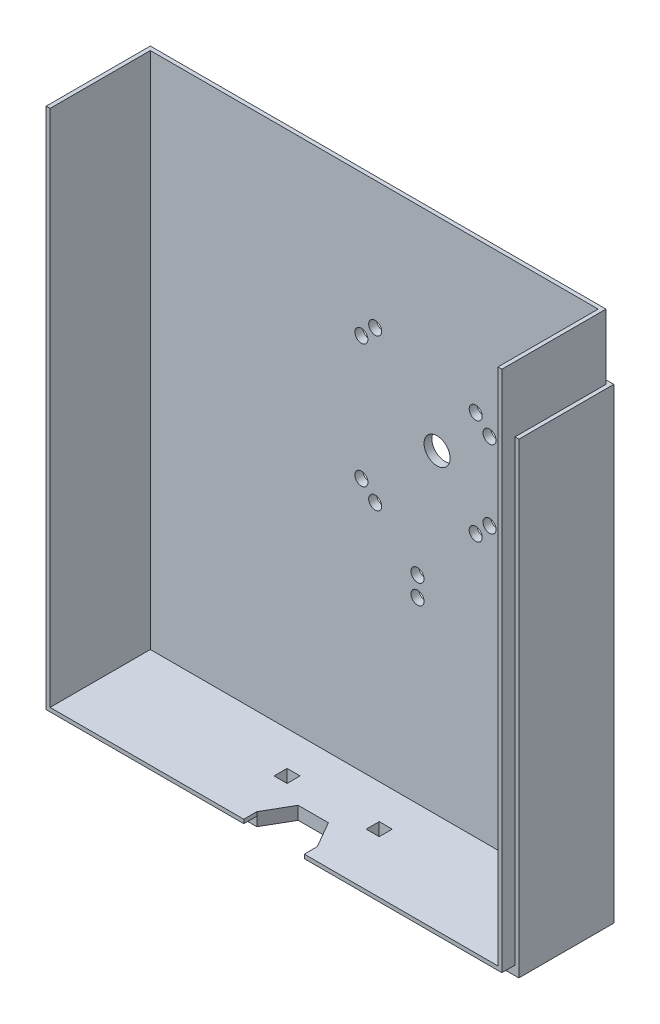
SolidWorks part; units mm, degrees
ref_plane "Front Plane" through (0, 0, 0) normal (0, 0, 1) x (1, 0, 0)
ref_plane "Top Plane" through (0, 0, 0) normal (0, 1, 0) x (1, 0, 0)
ref_plane "Right Plane" through (0, 0, 0) normal (1, 0, 0) x (0, 0, -1)
sketch "Sketch1" plane through (0, 0, 0) normal (0, 0, 1) x (1, 0, 0)
  line L1 (-88.9, -127) -> (88.9, -127)
  line L2 (-88.9, -127) -> (-88.9, 127)
  line L3 (-88.9, 127) -> (88.9, 127)
  line L4 (88.9, -127) -> (88.9, 127)
  line L5 (-88.9, -127) -> (88.9, 127) construction
  line L6 (-88.9, 127) -> (88.9, -127) construction
  point P0 (0, 0)
  dimension "D1" = 177.8
  dimension "D2" = 254
extrude "Boss-Extrude1" add sketch "Sketch1" along normal mid plane 72.89
shell "Shell1" thickness 3
sketch "Sketch2" plane through (0, 0, 33.445) normal (0, 0, -1) x (-1, 0, 0)
  line L0 (85.9, -124) -> (-85.9, -124) construction
  circle A0 centre (0, -4) radius 22
  dimension "D1" = 44
  dimension "D2" = 120
extrude "Cut-Extrude1" cut sketch "Sketch2" against normal blind 3
sketch "Sketch3" plane through (0, 0, -33.445) normal (0, 0, 1) x (1, 0, 0)
  line L0 (85.9, 124) -> (-85.9, 124) construction
  line L1 (-85.9, 124) -> (-85.9, -124) construction
  line L2 (44.2293, 13.826) -> (38.926, 19.1293) construction
  line L3 (-975.9, -1) -> (49024.1, -1) construction
  line L4 (24.1, -1) -> (41.5777, 16.4777) construction
  line L5 (-4.9352, 22.7319) -> (0.3681, 28.0352) construction
  line L6 (24.1, -1) -> (-2.2836, 25.3836) construction
  circle A0 centre (24.1, -1) radius 5
  circle A1 centre (24.1, -1) radius 25 construction
  circle A2 centre (44.2293, 13.826) radius 2.5
  circle A3 centre (38.926, 19.1293) radius 2.5
  circle A4 centre (38.926, -21.1293) radius 2.5
  circle A5 centre (44.2293, -15.826) radius 2.5
  circle A6 centre (24.1, -1) radius 37.5 construction
  circle A7 centre (0.3681, 28.0352) radius 2.5
  circle A8 centre (-4.9352, 22.7319) radius 2.5
  circle A9 centre (-4.9352, -24.7319) radius 2.5
  circle A10 centre (0.3681, -30.0352) radius 2.5
  circle A11 centre (16.6, -46) radius 2.5
  circle A12 centre (16.6, -53.5) radius 2.5
  dimension "D3" = 10
  dimension "D4" = 50
  dimension "D5" = 5
  dimension "D8" = 75
  dimension "D9" = 7.5
  dimension "D11" = 7.5
  dimension "D13" = 45
  dimension "D1" = 125
  dimension "D2" = 110
  dimension "D6" = 7.5
  dimension "D7" = 45
  dimension "D10" = 45
  dimension "D12" = 7.5
extrude "Cut-Extrude2" cut sketch "Sketch3" against normal blind 3
sketch "Sketch12" plane through (0, 124, 0) normal (0, -1, 0) x (1, 0, 0)
  line L0 (85.9, -33.445) -> (-85.9, -33.445) construction
  line L1 (6, 33.445) -> (-6, 33.445)
  line L2 (6, 33.445) -> (6, -33.445)
  line L3 (6, -33.445) -> (-6, -33.445)
  line L4 (-6, 33.445) -> (-6, -33.445)
  line L5 (6, 33.445) -> (-6, -33.445) construction
  line L6 (6, -33.445) -> (-6, 33.445) construction
  point P0 (0, 0)
  dimension "D1" = 12
extrude "Boss-Extrude5" add sketch "Sketch12" along normal blind 8
sketch "Sketch10" plane through (0, 127, 0) normal (0, 1, 0) x (1, 0, 0)
  circle A0 centre (0, 0) radius 3
  dimension "D1" = 6
extrude "Cut-Extrude8" cut sketch "Sketch10" against normal blind 8 contours A0
ref_plane "Plane2" through (0, 52, 0) normal (0, 1, 0) x (1, 0, 0)
split "Split2" trim tools "Plane2" bodies to split 123 resulting bodies 126 127
sketch "Sketch13" plane through (0, 52, 0) normal (0, 1, 0) x (1, 0, 0)
  line L4 (-85.9, 33.445) -> (-85.9, -33.445)
  line L5 (-85.9, -33.445) -> (85.9, -33.445)
  line L6 (85.9, -33.445) -> (85.9, 33.445)
  line L7 (85.9, 33.445) -> (-85.9, 33.445)
  line L8 (-87.4, 34.945) -> (-87.4, -34.945)
  line L9 (-87.4, -34.945) -> (87.4, -34.945)
  line L10 (87.4, -34.945) -> (87.4, 34.945)
  line L11 (87.4, 34.945) -> (-87.4, 34.945)
  line L12 (-87.4, 34.945) -> (-87.4, -34.945)
  line L13 (-87.4, -34.945) -> (87.4, -34.945)
  line L14 (87.4, -34.945) -> (87.4, 34.945)
  line L15 (87.4, 34.945) -> (-87.4, 34.945)
  dimension "D1" = 1.5
  dimension "D2" = 1.5
extrude "Boss-Extrude6" add sketch "Sketch13" along normal blind 25
sketch "Sketch14" plane through (0, 52, 0) normal (0, -1, 0) x (1, 0, 0)
  line L7 (-85.9, 33.445) -> (-85.9, -33.445)
  line L8 (-85.9, -33.445) -> (85.9, -33.445)
  line L9 (85.9, -33.445) -> (85.9, 33.445)
  line L10 (85.9, 33.445) -> (-85.9, 33.445)
  line L11 (-87.65, 35.195) -> (-87.65, -35.195)
  line L12 (-87.65, -35.195) -> (87.65, -35.195)
  line L13 (87.65, -35.195) -> (87.65, 35.195)
  line L14 (87.65, 35.195) -> (-87.65, 35.195)
  line L15 (-87.65, 35.195) -> (-87.65, -35.195)
  line L16 (-87.65, -35.195) -> (87.65, -35.195)
  line L17 (87.65, -35.195) -> (87.65, 35.195)
  line L18 (87.65, 35.195) -> (-87.65, 35.195)
  dimension "D1" = 1.75
  dimension "D2" = 1.75
extrude "Cut-Extrude9" cut sketch "Sketch14" against normal blind 10
sketch "Sketch17" plane through (0, -124, 0) normal (0, 1, 0) x (1, 0, 0)
  line L1 (-85.9, 33.445) -> (85.9, 33.445)
  line L2 (-85.9, 33.445) -> (-85.9, -33.445)
  line L3 (-85.9, -33.445) -> (85.9, -33.445)
  line L4 (85.9, 33.445) -> (85.9, -33.445)
  line L5 (-85.9, 33.445) -> (85.9, -33.445) construction
  line L6 (-85.9, -33.445) -> (85.9, 33.445) construction
  point P4 (0, 0)
extrude "Boss-Extrude7" add sketch "Sketch17" along normal blind 2
sketch "Sketch15" plane through (0, -127, 0) normal (0, -1, 0) x (1, 0, 0)
  line L0 (-1000, 0) -> (49000, 0) construction
  line L1 (11.6047, 0) -> (5.8024, 10.05)
  line L2 (5.8024, 10.05) -> (-5.8024, 10.05)
  line L3 (-5.8024, 10.05) -> (-11.6047, 0)
  line L4 (-11.6047, 0) -> (-5.8024, -10.05)
  line L5 (-5.8024, -10.05) -> (5.8024, -10.05)
  line L6 (5.8024, -10.05) -> (11.6047, 0)
  line L7 (-20.1777, 15.1777) -> (-15.1777, 15.1777)
  line L8 (-20.1777, 15.1777) -> (-20.1777, 20.1777)
  line L9 (-20.1777, 20.1777) -> (-15.1777, 20.1777)
  line L10 (-15.1777, 15.1777) -> (-15.1777, 20.1777)
  line L11 (-20.1777, 15.1777) -> (-15.1777, 20.1777) construction
  line L12 (-20.1777, 20.1777) -> (-15.1777, 15.1777) construction
  line L13 (0, 0) -> (-17.6777, 17.6777) construction
  line L14 (15.1777, 20.1777) -> (20.1777, 20.1777)
  line L15 (15.1777, 20.1777) -> (15.1777, 15.1777)
  line L16 (15.1777, 15.1777) -> (20.1777, 15.1777)
  line L17 (20.1777, 20.1777) -> (20.1777, 15.1777)
  line L18 (20.1777, -15.1777) -> (20.1777, -20.1777)
  line L19 (20.1777, -15.1777) -> (15.1777, -15.1777)
  line L20 (15.1777, -15.1777) -> (15.1777, -20.1777)
  line L21 (20.1777, -20.1777) -> (15.1777, -20.1777)
  line L22 (-15.1777, -20.1777) -> (-20.1777, -20.1777)
  line L23 (-15.1777, -20.1777) -> (-15.1777, -15.1777)
  line L24 (-15.1777, -15.1777) -> (-20.1777, -15.1777)
  line L25 (-20.1777, -20.1777) -> (-20.1777, -15.1777)
  line L26 (0, 0) -> (-15.1777, 15.1777) construction
  line L27 (0, 0) -> (15.1777, 15.1777) construction
  circle A1 centre (0, 0) radius 10.05 construction
  circle A2 centre (0, 0) radius 25 construction
  point P3 (-17.6777, 17.6777)
  dimension "D1" = 50
  dimension "D2" = 20.1
  dimension "D3" = 5
  dimension "D4" = 45
  dimension "D6" = 90
  dimension "D5" = 4
extrude "Cut-Extrude10" cut sketch "Sketch15" against normal blind 5
split "Split3" trim tools "Front Plane" bodies to split 137 resulting bodies 133 134
sketch "Sketch19" plane through (0, 0, 0) normal (0, 0, 1) x (1, 0, 0)
  line L0 (87.4, 52) -> (87.4, 77) construction
  line L1 (-87.4, 77) -> (-85.9, 77)
  line L2 (-87.4, 77) -> (-87.4, -123.5)
  line L3 (-87.4, -123.5) -> (-11.6047, -123.5)
  line L4 (87.4, 77) -> (87.4, -123.5)
  line L5 (-87.4, 77) -> (87.4, -123.5) construction
  line L6 (-87.4, -123.5) -> (87.4, 77) construction
  line L7 (-11.6047, -122) -> (-11.6047, -127) construction
  line L8 (-85.9, -122) -> (-11.6047, -122) construction
  line L9 (85.9, 77) -> (-85.9, 77) construction
  line L10 (-87.4, 77) -> (-87.4, 52) construction
  line L11 (-85.9, 75.5) -> (-85.9, -122)
  line L12 (-85.9, -122) -> (-11.6047, -122)
  line L13 (85.9, 75.5) -> (85.9, -122)
  line L15 (-11.6047, -122) -> (-11.6047, -123.5)
  line L17 (11.6047, -122) -> (11.6047, -123.5)
  line L19 (11.6047, -122) -> (85.9, -122)
  line L20 (-85.9, -122) -> (85.9, -122) construction
  line L21 (11.6047, -123.5) -> (87.4, -123.5)
  line L22 (-87.4, -123.5) -> (87.4, -123.5) construction
  line L23 (-85.9, 75.5) -> (-85.9, 77)
  line L24 (85.9, 75.5) -> (85.9, 77)
  line L25 (85.9, 77) -> (87.4, 77)
  line L26 (-87.4, 77) -> (87.4, 77) construction
  line L27 (-85.9, 75.5) -> (85.9, 75.5) construction
  line L28 (11.6047, -122) -> (11.6047, -127) construction
  point P4 (0, -23.25)
  dimension "D1" = 1.5
extrude "Boss-Extrude8" add sketch "Sketch19" along normal blind 5
delete or keep bodies "Body-Delete/Keep 1" type delete bodies bodies 129
delete or keep bodies "Body-Delete/Keep 2" type delete bodies bodies 133
